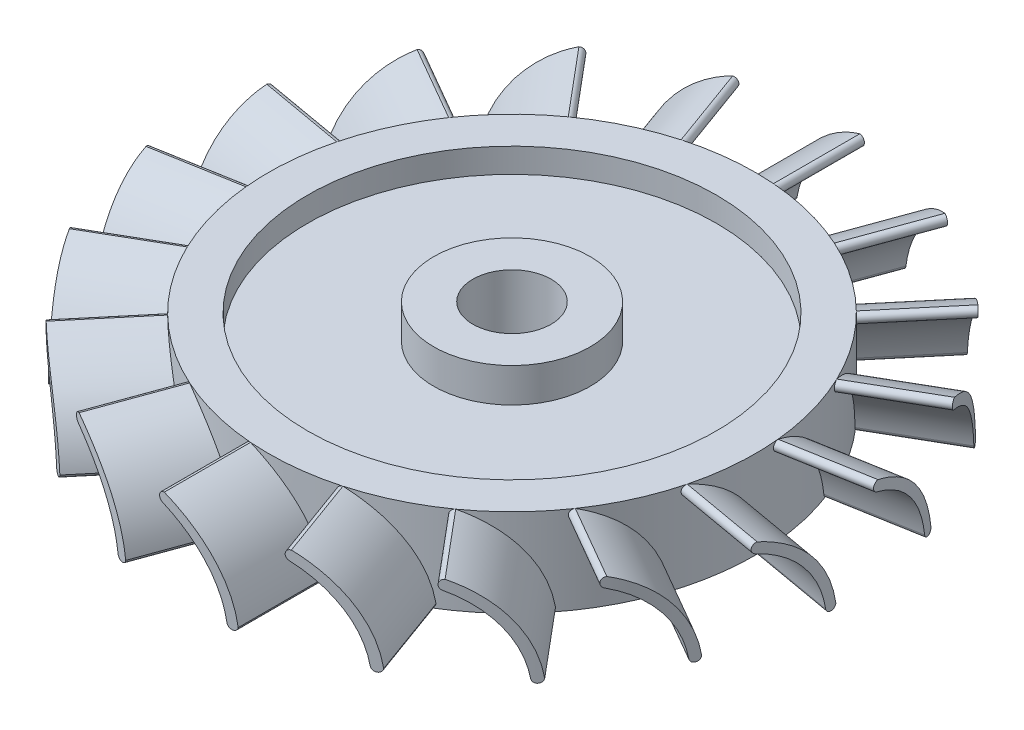
SolidWorks part; units mm, degrees
ref_plane "Ön Düzlem" through (0, 0, 0) normal (0, 0, 1) x (1, 0, 0)
ref_plane "Üst Düzlem" through (0, 0, 0) normal (0, 1, 0) x (1, 0, 0)
ref_plane "Sağ Düzlem" through (0, 0, 0) normal (1, 0, 0) x (0, 0, -1)
sketch "Çizim1" plane through (0, 0, 0) normal (0, 0, 1) x (1, 0, 0)
  line L0 (0, 0) -> (0, 37.0754) construction
  line L1 (-24.9, -3.9333) -> (-24.9, 5.0667)
  line L2 (-24.9, 5.0667) -> (-20.9, 5.0667)
  line L3 (-20.9, 5.0667) -> (-20.9, 2.5667)
  line L4 (-20.9, 2.5667) -> (-8, 2.5667)
  line L5 (-8, 2.5667) -> (-8, 6.0667)
  line L6 (-8, 6.0667) -> (-4, 6.0667)
  line L7 (-4, 6.0667) -> (-4, -3.9333)
  line L8 (-4, -3.9333) -> (-8, -3.9333)
  line L9 (-8, -3.9333) -> (-8, -1.4333)
  line L10 (-8, -1.4333) -> (-20.9, -1.4333)
  line L11 (-20.9, -1.4333) -> (-20.9, -3.9333)
  line L12 (-20.9, -3.9333) -> (-24.9, -3.9333)
  dimension "D1" = 24.9
  dimension "D2" = 10
  dimension "D3" = 9
  dimension "D4" = 4
  dimension "D5" = 4
  dimension "D6" = 2.5
  dimension "D7" = 4
  dimension "D8" = 4
  dimension "D9" = 2.5
  dimension "D10" = 20.9
  dimension "D11" = 12.9
revolve "Döndür1" add sketch "Çizim1" angle 360 about L0
ref_plane "Düzlem1" through (0, 0, 24) normal (0, 0, 1) x (1, 0, 0)
sketch "Çizim2" plane through (0, 0, 24) normal (0, 0, 1) x (1, 0, 0)
  line L0 (0, 0) -> (0, 15.7657) construction
  line L1 (24.9, 5.0667) -> (-24.9, 5.0667) construction
  line L2 (-24.9, -3.9333) -> (24.9, -3.9333) construction
  arc A1 (5.2881, -3.5067) -> (-1.913, 5.0667) centre (-5.1145, -4.9333) ccw
  arc A2 (4.2778, -3.5067) -> (-2.1065, 4.0779) centre (-5.1145, -4.9333) ccw
  arc A3 (-1.913, 5.0667) -> (-2.1065, 4.0779) centre (-1.913, 4.5534) ccw
  arc A4 (4.2778, -3.5067) -> (5.2881, -3.5067) centre (4.7829, -3.4208) ccw
  dimension "D1" = 10.5
  dimension "D2" = 9.5
  dimension "D3" = 0.5133
  dimension "D4" = 0.5124
  dimension "D5" = 4.2778
  dimension "D6" = 4.7829
extrude "Yükseklik-Ekstrüzyon4" add sketch "Çizim2" along normal blind 10.4
pattern_circular "Dairesel Kaplama1" count 18 over 360 about axis through (0, 0, 0) along (0, 1, 0) of "Yükseklik-Ekstrüzyon4"
sketch "Çizim3" plane through (0, 0, 0) normal (0, 0, 1) x (1, 0, 0)
  line L0 (0, 18.9) -> (0, -24.8272) construction
  line L1 (33.7, 19.6847) -> (33.7, -12.4152)
  line L2 (35.7, 19.6847) -> (35.7, -12.4152)
  line L3 (35.7, 19.6847) -> (33.7, 19.6847)
  line L4 (35.7, -12.4152) -> (33.7, -12.4152)
  dimension "D1" = 33.7
  dimension "D2" = 2
revolve "Kes-Döndür1" cut sketch "Çizim3" angle 360 about L0
